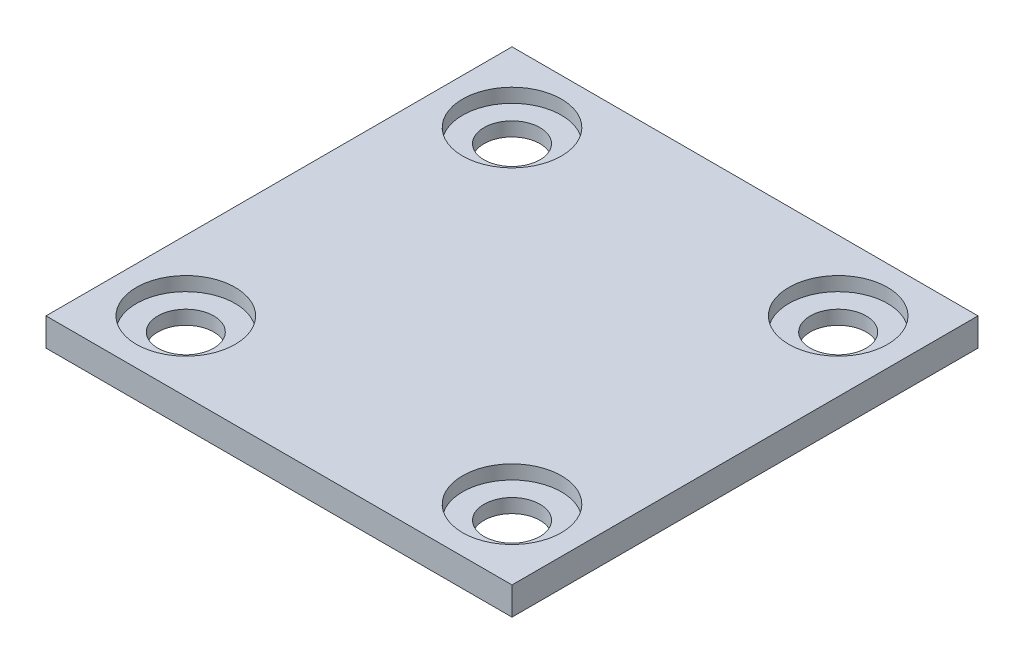
SolidWorks part; units mm, degrees
ref_plane "Front Plane" through (0, 0, 0) normal (0, 0, 1) x (1, 0, 0)
ref_plane "Top Plane" through (0, 0, 0) normal (0, 1, 0) x (1, 0, 0)
ref_plane "Right Plane" through (0, 0, 0) normal (1, 0, 0) x (0, 0, -1)
sketch "Sketch1" plane through (0, 0, 0) normal (0, 1, 0) x (1, 0, 0)
  line L1 (-17.5, -17.5) -> (17.5, -17.5) construction
  line L2 (-17.5, -17.5) -> (-17.5, 17.5) construction
  line L3 (-17.5, 17.5) -> (17.5, 17.5) construction
  line L4 (17.5, -17.5) -> (17.5, 17.5) construction
  line L5 (-17.5, -17.5) -> (17.5, 17.5) construction
  line L6 (-17.5, 17.5) -> (17.5, -17.5) construction
  line L7 (-25, -25) -> (25, -25)
  line L8 (-25, -25) -> (-25, 25)
  line L9 (-25, 25) -> (25, 25)
  line L10 (25, -25) -> (25, 25)
  line L11 (-25, -25) -> (25, 25) construction
  line L12 (-25, 25) -> (25, -25) construction
  circle A0 centre (-17.5, 17.5) radius 3
  circle A1 centre (17.5, 17.5) radius 3
  circle A2 centre (-17.5, -17.5) radius 3
  circle A3 centre (17.5, -17.5) radius 3
  circle A4 centre (-17.5, 17.5) radius 5.25 construction
  point P0 (0, 0)
  point P10 (0, 0)
  dimension "D3" = 6
  dimension "D5" = 10.5
  dimension "D1" = 35
  dimension "D2" = 35
  dimension "D4" = 50
extrude "Boss-Extrude1" add sketch "Sketch1" along normal blind 3
sketch "Sketch2" plane through (0, 3, 0) normal (0, 1, 0) x (1, 0, 0)
  circle A0 centre (-17.5, 17.5) radius 5.3
  circle A1 centre (17.5, 17.5) radius 5.3
  circle A2 centre (17.5, -17.5) radius 5.3
  circle A3 centre (-17.5, -17.5) radius 5.3
  dimension "D1" = 10.6
extrude "Cut-Extrude1" cut sketch "Sketch2" against normal blind 1.5
